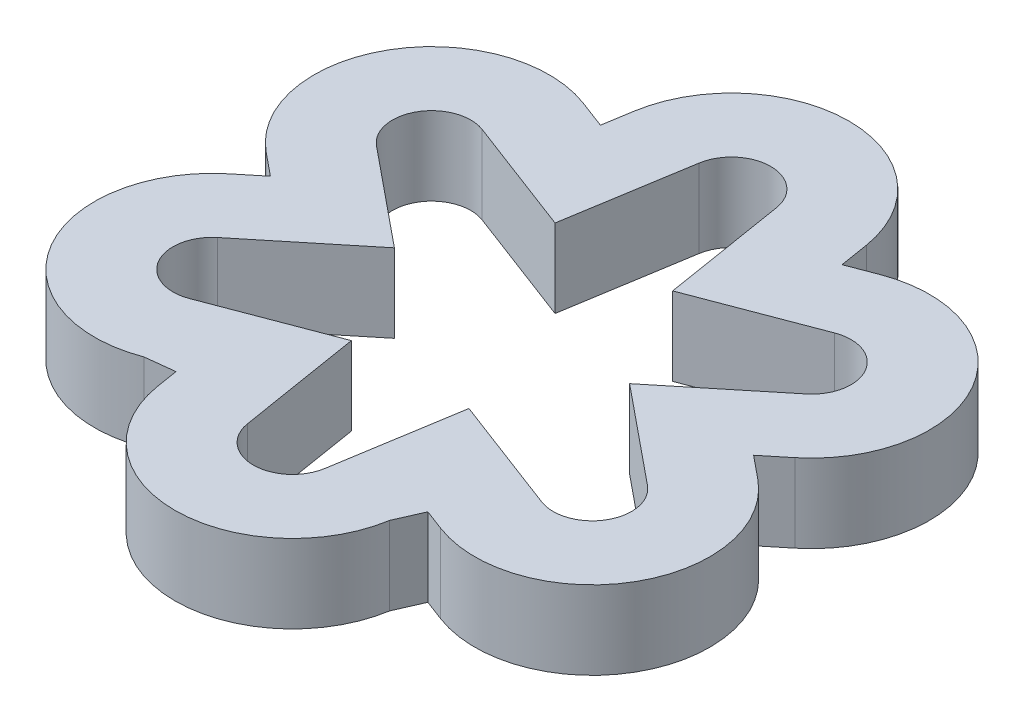
SolidWorks part; units mm, degrees
ref_plane "Front Plane" through (0, 0, 0) normal (0, 0, 1) x (1, 0, 0)
ref_plane "Top Plane" through (0, 0, 0) normal (0, 1, 0) x (1, 0, 0)
ref_plane "Right Plane" through (0, 0, 0) normal (1, 0, 0) x (0, 0, -1)
sketch "Sketch1" plane through (0, 0, 0) normal (0, 1, 0) x (1, 0, 0)
  line L0 (0, 0) -> (0, 14) construction
  line L1 (0, 0) -> (0, 6.5) construction
  line L2 (-3.75, 6.5) -> (3.75, 6.5) construction
  line L3 (-3.75, 6.5) -> (-2.4677, 14.4005)
  line L4 (2.4677, 14.4005) -> (3.75, 6.5)
  line L5 (-7.7045, 13.3446) -> (-7.4031, 15.2016)
  line L6 (7.4031, 15.2016) -> (7.7045, 13.3446)
  line L7 (7.7045, 13.3446) -> (9.4634, 14.0121)
  line L8 (16.8665, 1.1895) -> (15.409, 0)
  line L9 (13.7051, 5.0632) -> (7.5042, 0.0024)
  line L10 (3.7542, 6.4976) -> (11.2374, 9.3374)
  line L11 (15.409, 0) -> (16.8665, -1.1895)
  line L12 (9.4634, -14.0121) -> (8.1458, -13.5121)
  line L13 (11.2374, -9.3374) -> (3.7542, -6.4976)
  line L14 (7.5042, -0.0024) -> (13.7051, -5.0632)
  line L15 (-7.5042, 0.0024) -> (-7.5042, -0.0024)
  line L16 (-7.4031, -15.2016) -> (-7.6305, -13.8005)
  line L17 (-2.4677, -14.4005) -> (-3.75, -6.5)
  line L18 (3.75, -6.5) -> (2.4677, -14.4005)
  line L19 (-3.75, 6.5) -> (-3.7542, 6.4976)
  line L20 (-16.8665, -1.1895) -> (-15.409, 0)
  line L21 (-13.7051, -5.0632) -> (-7.5042, -0.0024)
  line L22 (-3.7542, -6.4976) -> (-11.2374, -9.3374)
  line L23 (-15.409, 0) -> (-16.8665, 1.1895)
  line L24 (-9.4634, 14.0121) -> (-7.7045, 13.3446)
  line L25 (-11.2374, 9.3374) -> (-3.7542, 6.4976)
  line L26 (-7.5042, 0.0024) -> (-13.7051, 5.0632)
  line L27 (-8.6854, 7.301) -> (-7.4031, 15.2016) construction
  line L28 (3.7542, 6.4976) -> (3.75, 6.5)
  line L29 (7.4031, 15.2016) -> (8.6854, 7.301) construction
  line L30 (8.1458, -13.5121) -> (7.4031, -15.2016)
  line L31 (-7.6305, -13.8005) -> (-9.4634, -14.0121)
  line L32 (7.5042, -0.0024) -> (7.5042, 0.0024)
  line L33 (-1.8253, -11.1136) -> (-3.0966, -11.596) [skipped]
  line L34 (8.7119, -7.1376) -> (8.4941, -8.4797) [skipped]
  line L35 (3.75, -6.5) -> (3.7542, -6.4976)
  line L36 (-3.7542, -6.4976) -> (-3.75, -6.5)
  arc A0 (2.4677, 14.4005) -> (-2.4677, 14.4005) centre (0, 14) ccw
  arc A1 (7.4031, 15.2016) -> (-7.4031, 15.2016) centre (0, 14) ccw
  arc A2 (16.8665, 1.1895) -> (9.4634, 14.0121) centre (12.1244, 7) ccw
  arc A3 (13.7051, 5.0632) -> (11.2374, 9.3374) centre (12.1244, 7) ccw
  arc A4 (9.4634, -14.0121) -> (16.8665, -1.1895) centre (12.1244, -7) ccw
  arc A5 (11.2374, -9.3374) -> (13.7051, -5.0632) centre (12.1244, -7) ccw
  arc A6 (-7.4031, -15.2016) -> (7.4031, -15.2016) centre (0, -14) ccw
  arc A7 (-2.4677, -14.4005) -> (2.4677, -14.4005) centre (0, -14) ccw
  arc A8 (-16.8665, -1.1895) -> (-9.4634, -14.0121) centre (-12.1244, -7) ccw
  arc A9 (-13.7051, -5.0632) -> (-11.2374, -9.3374) centre (-12.1244, -7) ccw
  arc A10 (-9.4634, 14.0121) -> (-16.8665, 1.1895) centre (-12.1244, 7) ccw
  arc A11 (-11.2374, 9.3374) -> (-13.7051, 5.0632) centre (-12.1244, 7) ccw
  point P7 (0, 6.5)
  point P66 (0, 0)
  point P77 (0, 0)
  dimension "D4" = 5
  dimension "D1" = 14
  dimension "D2" = 6.5
  dimension "D3" = 7.5
  dimension "D5" = 5
  dimension "D6" = 6
  dimension "D7" = 6
extrude "Boss-Extrude1" add sketch "Sketch1" along normal blind 5 contours L24 A10 L23 L20 A8 L31 L16 A6 L30 L12 A4 L11 L8 A2 L7 L6 A1 L5 A11 L25 L19 L3 A0 L4 L28 L10 A3 L9 L32 L14 A5 L13 L35 L18 A7 L17 L36 L22 A9 L21 L15 L26
